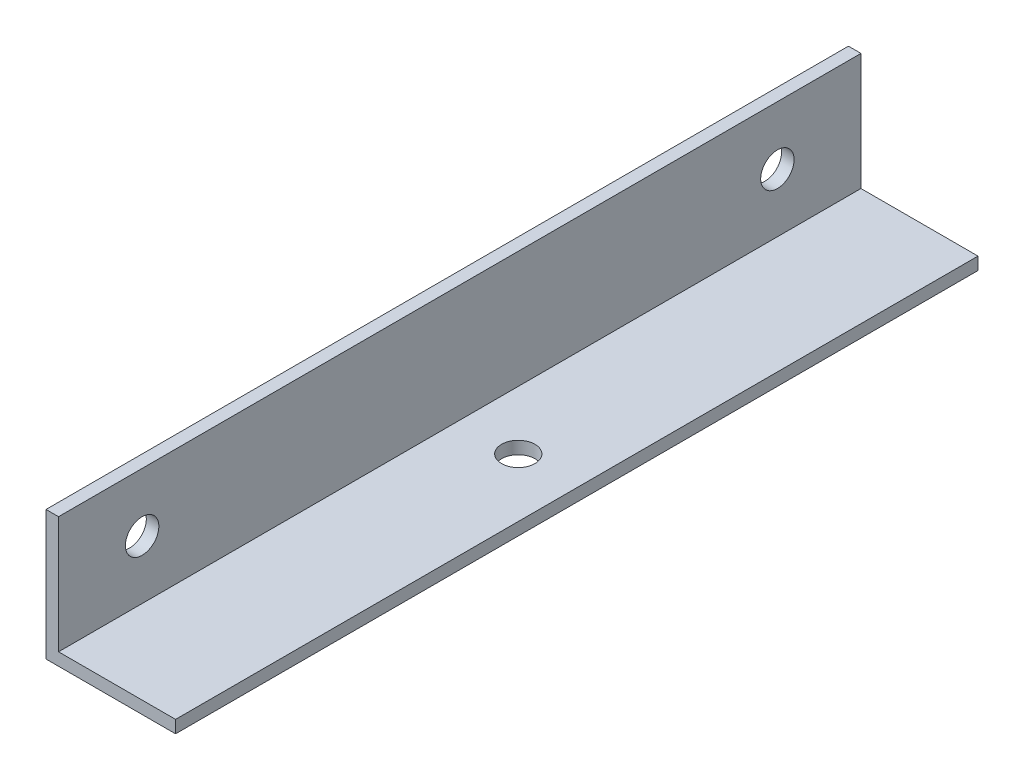
SolidWorks part; units mm, degrees
material "3.0205 (EN-AW 1200)"
ref_plane "Plan de face" through (0, 0, 0) normal (0, 0, 1) x (1, 0, 0)
ref_plane "Plan de dessus" through (0, 0, 0) normal (0, 1, 0) x (1, 0, 0)
ref_plane "Plan de droite" through (0, 0, 0) normal (1, 0, 0) x (0, 0, -1)
sketch "Esquisse1" plane through (0, 0, 0) normal (0, 0, 1) x (1, 0, 0)
  line L0 (0, 15.5) -> (0, 0)
  line L1 (0, 0) -> (15.5, 0)
  dimension "D1" = 15.5
  dimension "D2" = 15.5
extrude "Extru.-Mince1" add sketch "Esquisse1" along normal blind 96 thin thin type one direction reverse wall 1.5
sketch "Esquisse2" plane through (1.5, 0, 0) normal (1, 0, 0) x (0, 0, -1)
  line L0 (-48, 15.5) -> (-48, 0) construction
  line L1 (-96, 15.5) -> (0, 15.5) construction
  line L2 (-96, 0) -> (0, 0) construction
  line L3 (-96, 15.5) -> (-96, 1.5) construction
  circle A0 centre (-86, 8.5) radius 2
  circle A1 centre (-10, 8.5) radius 2
  point P12 (-96, 8.5)
  dimension "D1" = 4
  dimension "D2" = 76
extrude "Enlèv. mat.-Extru.1" cut sketch "Esquisse2" against normal through all
sketch "Esquisse3" plane through (0, 1.5, 0) normal (0, 1, 0) x (1, 0, 0)
  line L0 (1.5, 0) -> (15.5, 0) construction
  line L1 (15.5, -96) -> (15.5, 0) construction
  circle A0 centre (8.5, -48) radius 2
  point P4 (8.5, 0)
  point P7 (15.5, -48)
  dimension "D1" = 4
extrude "Enlèv. mat.-Extru.2" cut sketch "Esquisse3" against normal through all
